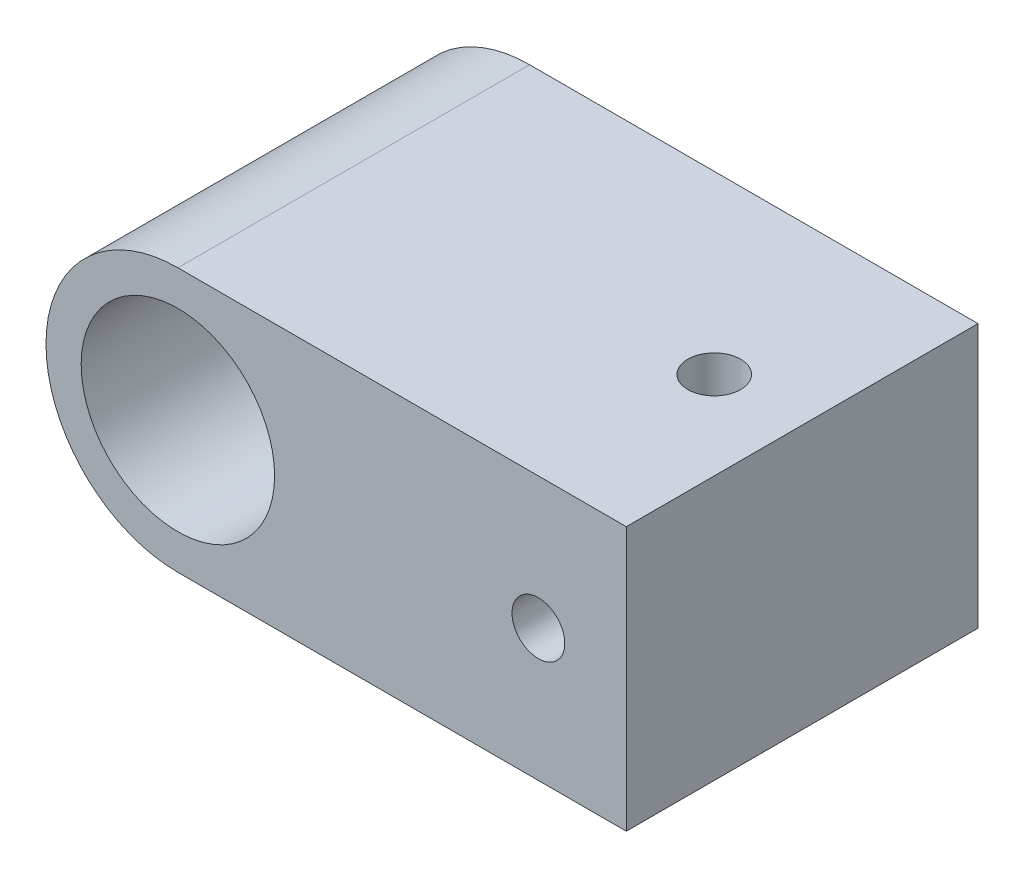
SolidWorks part; units mm, degrees
ref_plane "Front Plane" through (0, 0, 0) normal (0, 0, 1) x (1, 0, 0)
ref_plane "Top Plane" through (0, 0, 0) normal (0, 1, 0) x (1, 0, 0)
ref_plane "Right Plane" through (0, 0, 0) normal (1, 0, 0) x (0, 0, -1)
sketch "Sketch1" plane through (0, 0, 0) normal (0, 0, 1) x (1, 0, 0)
  circle A0 centre (0, 0) radius 7.5
  dimension "D1" = 15
extrude "Boss-Extrude1" add sketch "Sketch1" along normal blind 20
sketch "Sketch2" plane through (0, 0, 0) normal (1, 0, 0) x (0, 0, -1)
  line L0 (-20, 7.5) -> (-20, -7.5) construction
  line L1 (-20, 7.5) -> (0, 7.5)
  line L2 (-20, 7.5) -> (-20, -7.5)
  line L3 (-20, -7.5) -> (0, -7.5)
  line L4 (0, 7.5) -> (0, -7.5)
extrude "Boss-Extrude2" add sketch "Sketch2" along normal blind 25.5
sketch "Sketch3" plane through (0, 0, 20) normal (0, 0, 1) x (1, 0, 0)
  circle A0 centre (0, 0) radius 5.5
  dimension "D1" = 11
extrude "Cut-Extrude1" cut sketch "Sketch3" against normal blind 26
sketch "Sketch4" plane through (0, 7.5, 0) normal (0, 1, 0) x (1, 0, 0)
  line L0 (25.5, 0) -> (25.5, -20) construction
  circle A0 centre (20.5, -10) radius 1.5
  point P2 (25.5, -10)
  dimension "D1" = 3
  dimension "D2" = 5
extrude "Cut-Extrude2" cut sketch "Sketch4" against normal blind 30
sketch "Sketch5" plane through (0, 0, 0) normal (0, 0, -1) x (-1, 0, 0)
  line L0 (-25.5, 7.5) -> (-25.5, -7.5) construction
  circle A0 centre (-20.5, 0) radius 1.5
  point P2 (-25.5, 0)
  dimension "D1" = 3
  dimension "D2" = 5
extrude "Cut-Extrude3" cut sketch "Sketch5" against normal blind 30
